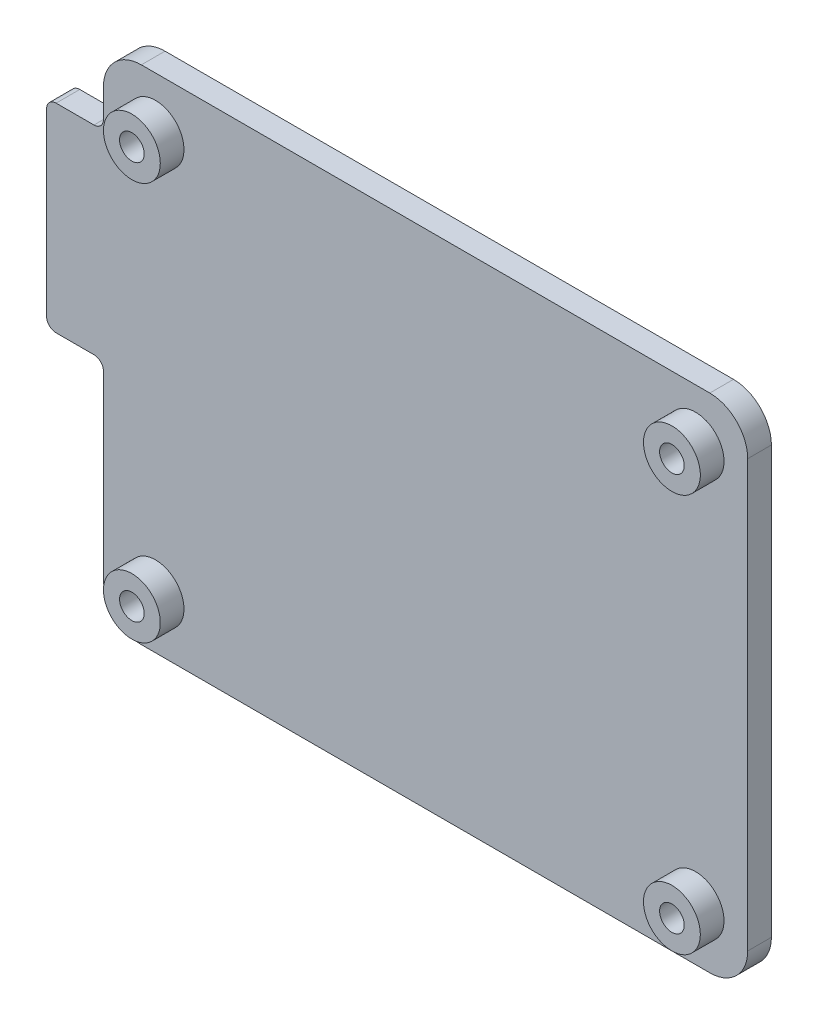
SolidWorks part; units mm, degrees
material "ABS"
ref_plane "Plano frontal" through (0, 0, 0) normal (0, 0, 1) x (1, 0, 0)
ref_plane "Plano superior" through (0, 0, 0) normal (0, 1, 0) x (1, 0, 0)
ref_plane "Plano direito" through (0, 0, 0) normal (1, 0, 0) x (0, 0, -1)
sketch "Esboço1" plane through (0, 0, 0) normal (0, 0, 1) x (1, 0, 0)
  line L1 (-34, -26.5) -> (34, -26.5)
  line L2 (-34, -26.5) -> (-34, 26.5)
  line L3 (-34, 26.5) -> (34, 26.5)
  line L4 (34, -26.5) -> (34, 26.5)
  line L5 (-34, -26.5) -> (34, 26.5) construction
  line L6 (-34, 26.5) -> (34, -26.5) construction
  point P0 (0, 0)
  dimension "D1" = 68
  dimension "D2" = 53
extrude "Ressalto-extrusão1" add sketch "Esboço1" along normal blind 2.5
sketch "Esboço2" plane through (0, 0, 2.5) normal (0, 0, 1) x (1, 0, 0)
  line L0 (0, 26.5) -> (0, -26.5) construction
  line L1 (34, 26.5) -> (-34, 26.5) construction
  line L2 (-34, -26.5) -> (34, -26.5) construction
  line L3 (-34, 0) -> (34, 0) construction
  line L4 (-34, 26.5) -> (-34, -26.5) construction
  line L5 (34, -26.5) -> (34, 26.5) construction
  circle A0 centre (-28.5, 21) radius 3
  circle A1 centre (-28.5, -21) radius 3
  circle A2 centre (28.5, -21) radius 3
  circle A3 centre (28.5, 21) radius 3
  circle A4 centre (-28.5, 21) radius 1.3
  circle A5 centre (28.5, 21) radius 1.3
  circle A6 centre (28.5, -21) radius 1.3
  circle A7 centre (-28.5, -21) radius 1.3
  dimension "D1" = 28.5
  dimension "D2" = 21
  dimension "D3" = 6
  dimension "D4" = 2.6
extrude "Ressalto-extrusão2" add sketch "Esboço2" along normal blind 2.5
fillet "Filete1" radius 4 4 edges at (-34, -26.5, 1.25) (34, -26.5, 1.25) (34, 26.5, 1.25) (-34, 26.5, 1.25)
sketch "Esboço13" plane through (0, 0, 2.5) normal (0, 0, 1) x (1, 0, 0)
  line L0 (0, 26.5) -> (0, -26.5) construction
  line L1 (30, 26.5) -> (-30, 26.5) construction
  line L2 (-30, -26.5) -> (30, -26.5) construction
  line L3 (-34, 0) -> (34, 0) construction
  line L4 (-34, 22.5) -> (-34, -22.5) construction
  line L5 (34, -22.5) -> (34, 22.5) construction
  circle A0 centre (-28.5, 21) radius 2.2
  circle A1 centre (-28.5, -21) radius 2.2
  circle A2 centre (28.5, -21) radius 2.2
  circle A3 centre (28.5, 21) radius 2.2
  dimension "D1" = 4.4
extrude "Corte-extrusão1" cut sketch "Esboço13" against normal through all from offset 0.7 offset against normal yes
sketch "Esboço14" plane through (0, 0, 2.5) normal (0, 0, 1) x (1, 0, 0)
  circle A0 centre (-28.5, 21) radius 1.3
  circle A1 centre (28.5, 21) radius 1.3
  circle A2 centre (28.5, -21) radius 1.3
  circle A3 centre (-28.5, -21) radius 1.3
extrude "Corte-extrusão2" cut sketch "Esboço14" against normal through all
sketch "Esboço16" plane through (0, 0, 2.5) normal (0, 0, 1) x (1, 0, 0)
  line L0 (-34, 22.5) -> (-34, -22.5) construction
  line L1 (-34, 18.5) -> (-40, 18.5)
  line L2 (-34, 18.5) -> (-34, -2.5)
  line L3 (-34, -2.5) -> (-40, -2.5)
  line L4 (-40, 18.5) -> (-40, -2.5)
  line L5 (30, 26.5) -> (-30, 26.5) construction
  dimension "D1" = 6
  dimension "D2" = 21
  dimension "D3" = 8
extrude "Ressalto-extrusão4" add sketch "Esboço16" against normal through all
fillet "Filete2" radius 1 4 edges at (-40, -2.5, 1.25) (-40, 18.5, 1.25) (-34, -2.5, 1.25) (-34, 18.5, 1.25)
